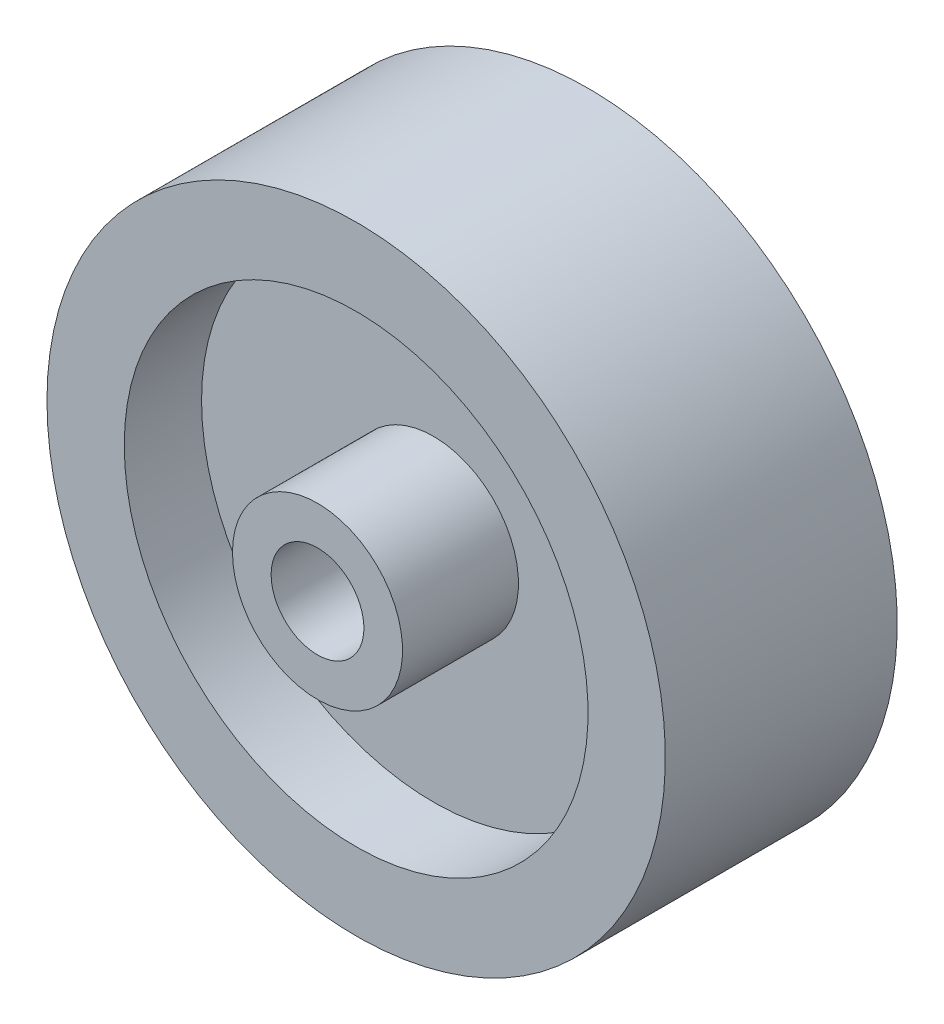
SolidWorks part; units mm, degrees
material "Бутил"
ref_plane "Спереди (XY)" through (0, 0, 0) normal (0, 0, 1) x (1, 0, 0)
ref_plane "Сверху (XZ)" through (0, 0, 0) normal (0, 1, 0) x (1, 0, 0)
ref_plane "Справа (ZY)" through (0, 0, 0) normal (1, 0, 0) x (0, 0, -1)
sketch "Эскиз1" plane through (0, 0, 0) normal (0, 1, 0) x (1, 0, 0)
  line L0 (-6, -20) -> (-6, 20)
  line L1 (-6, 20) -> (-11, 20)
  line L2 (-11, 20) -> (-11, 5)
  line L3 (-11, 5) -> (-30, 5)
  line L4 (-30, 5) -> (-30, 15)
  line L5 (-30, 15) -> (-40, 15)
  line L6 (-40, 15) -> (-40, -15)
  line L7 (0, 0) -> (-40, 0) construction
  line L8 (-30, -15) -> (-40, -15)
  line L9 (-30, -5) -> (-30, -15)
  line L10 (-11, -5) -> (-30, -5)
  line L11 (-11, -20) -> (-11, -5)
  line L12 (-6, -20) -> (-11, -20)
  line L13 (0, 39.6203) -> (0, -64.2182) construction
  point P16 (-6, 0)
  dimension "D1" = 40
  dimension "D2" = 30
  dimension "D3" = 10
  dimension "D4" = 5
  dimension "D5" = 10
  dimension "D6" = 34
  dimension "D7" = 6
revolve "Повернуть1" add sketch "Эскиз1" angle 360 about L13
